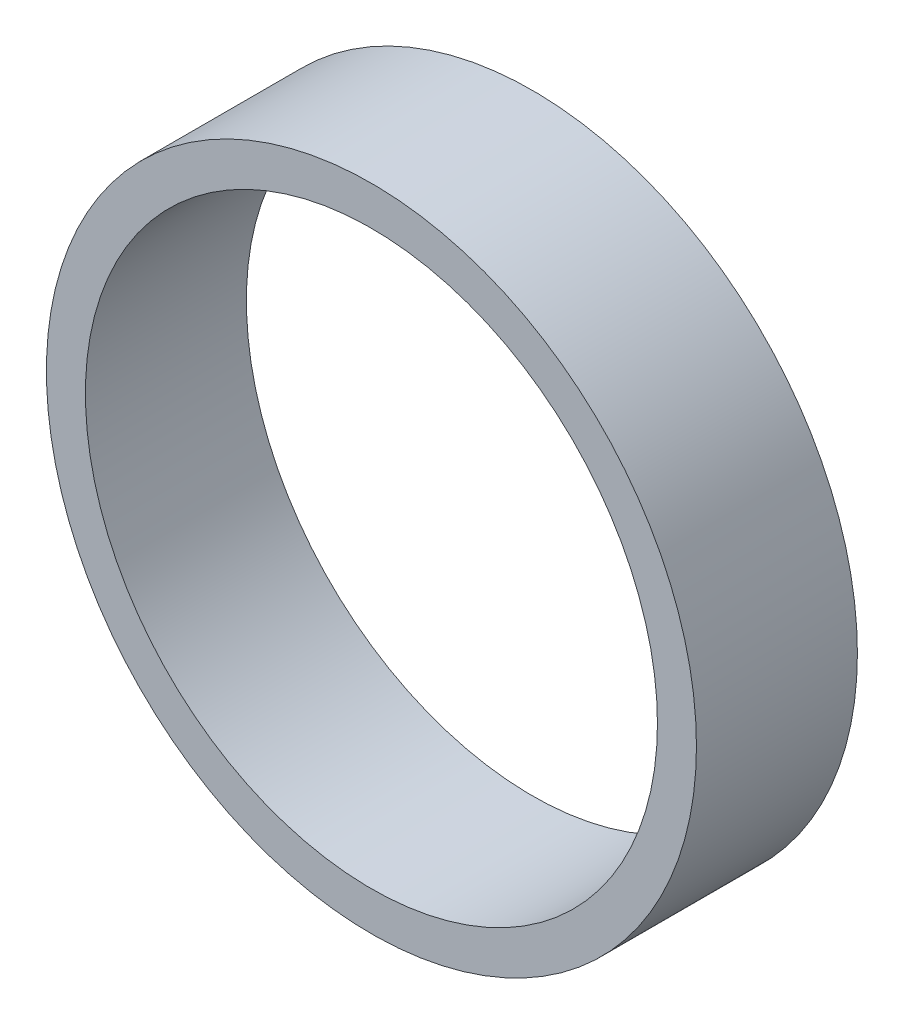
SolidWorks part; units mm, degrees
material "Rubber"
ref_plane "Front Plane" through (0, 0, 0) normal (0, 0, 1) x (1, 0, 0)
ref_plane "Top Plane" through (0, 0, 0) normal (0, 1, 0) x (1, 0, 0)
ref_plane "Right Plane" through (0, 0, 0) normal (1, 0, 0) x (0, 0, -1)
sketch "Sketch1" plane through (0, 0, 0) normal (0, 0, 1) x (1, 0, 0)
  circle A0 centre (0, 0) radius 22 construction
  circle A1 centre (0, 0) radius 22
  circle A2 centre (0, 0) radius 25 construction
  circle A3 centre (0, 0) radius 25
extrude "Boss-Extrude1" add sketch "Sketch1" against normal up to surface (12.38 mm away)
